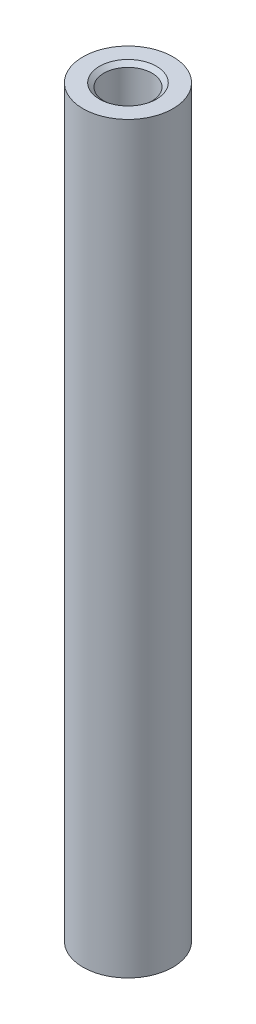
SolidWorks part; units mm, degrees
material "6061 Alloy"
ref_plane "Front" through (0, 0, 0) normal (0, 0, 1) x (1, 0, 0)
ref_plane "Top" through (0, 0, 0) normal (0, 1, 0) x (1, 0, 0)
ref_plane "Right" through (0, 0, 0) normal (1, 0, 0) x (0, 0, -1)
sketch "Sketch1" plane through (0, 0, 0) normal (0, 1, 0) x (1, 0, 0)
  circle A0 centre (0, 0) radius 6.35
  dimension "D1" = 12.7
extrude "Boss-Extrude1" add sketch "Sketch1" along normal blind 104.9782
hole_wizard "M8x1.25 Tapped Hole1" positions "Sketch2" profile "Sketch3" tap size "M8x1.25" standard "ANSI Metric"
sketch "Sketch2" plane through (0, 104.9782, 0) normal (0, 1, 0) x (1, 0, 0)
  point P0 (0, 0)
sketch "Sketch3" plane through (0, 104.9782, 0) normal (1, 0, 0) x (0, 0, 1)
  line L0 (0, 0) -> (0, 21.8041)
  line L1 (0, 21.8041) -> (3.4, 19.7612)
  line L2 (3.4, 19.7612) -> (3.4, 0.5244)
  line L3 (3.4, 0.5244) -> (4.025, 0)
  line L5 (4.025, 0) -> (0, 0)
  line L6 (-3.4, 0.5244) -> (-4.025, 0) construction
  line L10 (0, 21.8041) -> (-3.4, 19.7612) construction
  line L11 (0, -6.35) -> (0, 107.95) construction
  dimension "Tap Drill Dia." = 6.8
  dimension "Tap Drill Depth" = 19.7612
  dimension "Near C'Sink Dia." = 8.05
  dimension "Near C'Sink Angle" = 100
  dimension "Drill Angle" = 118
cosmetic thread "Hole Thread1" parameters "D1"=16.002, "D2"=8
hole_wizard "1/4-20 Tapped Hole1" positions "Sketch4" profile "Sketch5" tap size "1/4-20" standard "ANSI Inch"
sketch "Sketch4" plane through (0, 0, 0) normal (0, -1, 0) x (-1, 0, 0)
  point P0 (0, 0)
sketch "Sketch5" plane through (0, 0, 0) normal (1, 0, 0) x (0, 0, -1)
  line L0 (0, 0) -> (0, 18.0438)
  line L1 (0, 18.0438) -> (2.5527, 16.51)
  line L2 (2.5527, 16.51) -> (2.5527, 1.055)
  line L3 (2.5527, 1.055) -> (3.81, 0)
  line L5 (3.81, 0) -> (0, 0)
  line L6 (-2.5527, 1.055) -> (-3.81, 0) construction
  line L10 (0, 18.0438) -> (-2.5527, 16.51) construction
  line L11 (0, -6.35) -> (0, 107.95) construction
  dimension "Tap Drill Dia." = 5.1054
  dimension "Tap Drill Depth" = 16.51
  dimension "Near C'Sink Dia." = 7.62
  dimension "Near C'Sink Angle" = 100
  dimension "Drill Angle" = 118
cosmetic thread "Hole Thread2" parameters "D1"=12.7, "D2"=6.35
